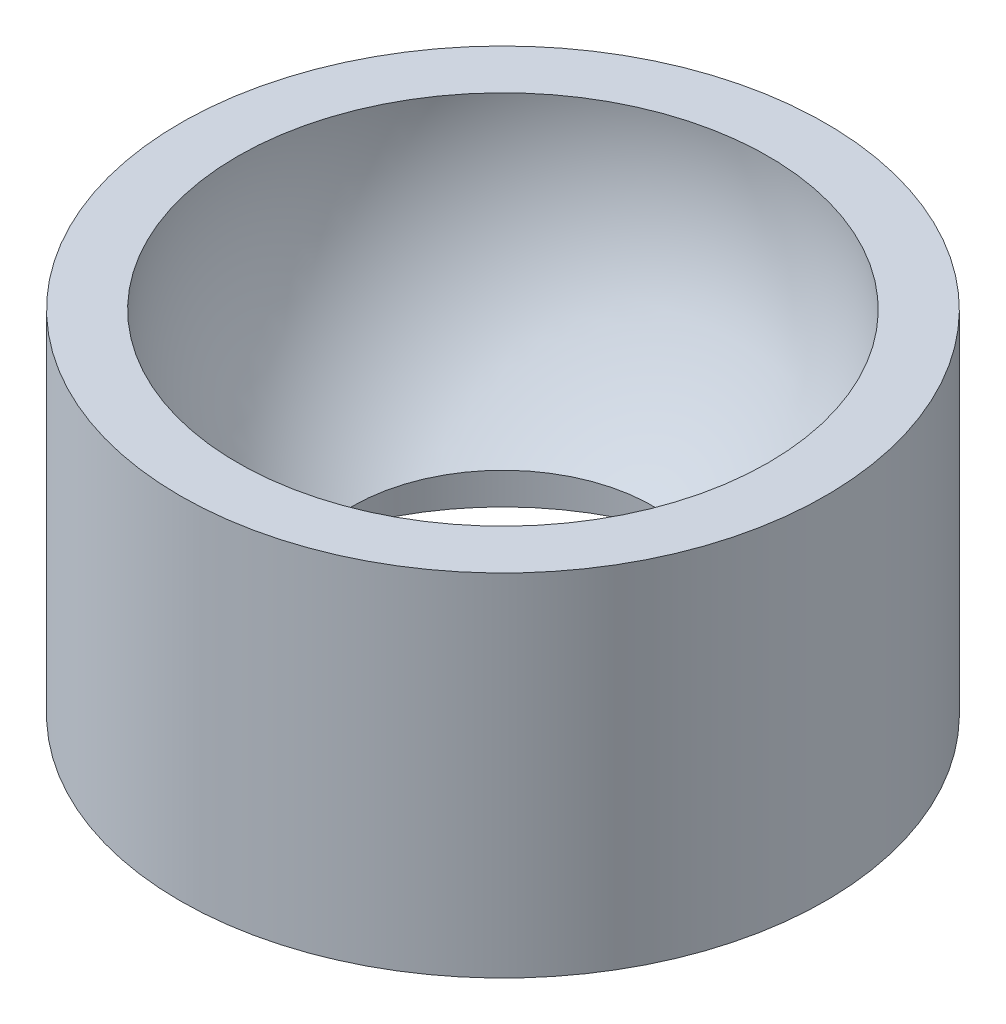
SolidWorks part; units mm, degrees
ref_plane "Front Plane" through (0, 0, 0) normal (0, 0, 1) x (1, 0, 0)
ref_plane "Top Plane" through (0, 0, 0) normal (0, 1, 0) x (1, 0, 0)
ref_plane "Right Plane" through (0, 0, 0) normal (1, 0, 0) x (0, 0, -1)
sketch "Sketch1" plane through (0, 0, 0) normal (0, 1, 0) x (1, 0, 0)
  circle A0 centre (0, 0) radius 92
  dimension "D1" = 184
extrude "Boss-Extrude1" add sketch "Sketch1" along normal blind 100
sketch "Sketch2" plane through (0, 0, 0) normal (0, 0, 1) x (1, 0, 0)
  line L3 (0, 16.7444) -> (0, 168.7444)
  arc A1 (0, 168.7444) -> (0, 16.7444) centre (0, 92.7444) ccw
  dimension "D1" = 152
revolve "Cut-Revolve1" cut sketch "Sketch2" angle 360 about L3
sketch "Sketch3" plane through (0, 0, 0) normal (0, -1, 0) x (1, 0, 0)
  circle A0 centre (0, 0) radius 72.5
  dimension "D1" = 145
extrude "Cut-Extrude1" cut sketch "Sketch3" against normal blind 30
